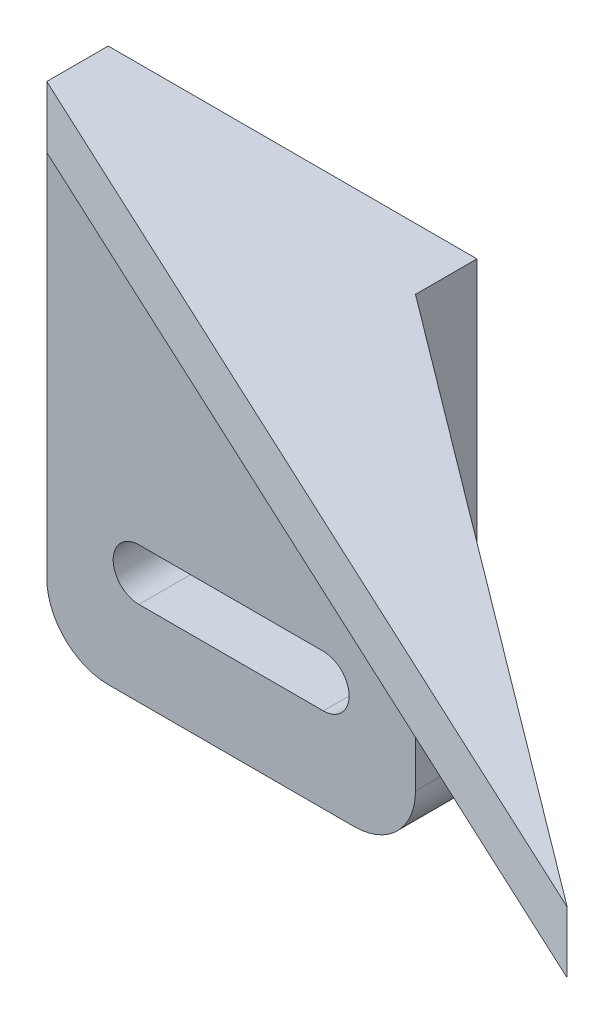
SolidWorks part; units mm, degrees
ref_plane "Front Plane" through (0, 0, 0) normal (0, 0, 1) x (1, 0, 0)
ref_plane "Top Plane" through (0, 0, 0) normal (0, 1, 0) x (1, 0, 0)
ref_plane "Right Plane" through (0, 0, 0) normal (1, 0, 0) x (0, 0, -1)
sketch "Sketch1" plane through (0, 0, 0) normal (0, 0, 1) x (1, 0, 0)
  line L1 (15, -20) -> (-15, -20)
  line L2 (15, -20) -> (15, 20)
  line L3 (15, 20) -> (-15, 20)
  line L4 (-15, -20) -> (-15, 20)
  line L5 (15, -20) -> (-15, 20) construction
  line L6 (15, 20) -> (-15, -20) construction
  point P0 (0, 0)
  dimension "D1" = 40
  dimension "D2" = 30
extrude "Boss-Extrude1" add sketch "Sketch1" along normal blind 5
sketch "Sketch2" plane through (0, 20, 0) normal (0, 1, 0) x (1, 0, 0)
  line L0 (-15, -5) -> (64.3468, -42)
  line L1 (64.3468, -42) -> (15, -5)
  line L2 (-15, -5) -> (15, -5)
  dimension "D1" = 37
  dimension "D2" = 25
extrude "Boss-Extrude2" add sketch "Sketch2" against normal blind 5
fillet "Fillet1" radius 5 2 edges at (15, -20, 2.5) (-15, -20, 2.5)
sketch "Sketch3" plane through (0, 0, 0) normal (0, 0, -1) x (-1, 0, 0)
  line L0 (0, 0) -> (0, -20) construction
  line L1 (10, -20) -> (-10, -20) construction
  line L2 (7.5, -11) -> (-7.5, -11) construction
  line L3 (7.5, -13.1) -> (-7.5, -13.1)
  line L4 (7.5, -8.9) -> (-7.5, -8.9)
  arc A0 (7.5, -13.1) -> (7.5, -8.9) centre (7.5, -11) ccw
  arc A1 (-7.5, -8.9) -> (-7.5, -13.1) centre (-7.5, -11) ccw
  point P7 (0, -11)
  point P12 (0, 0)
  dimension "D1" = 11
  dimension "D2" = 4.2
  dimension "D3" = 15
extrude "Cut-Extrude1" cut sketch "Sketch3" against normal blind 5
